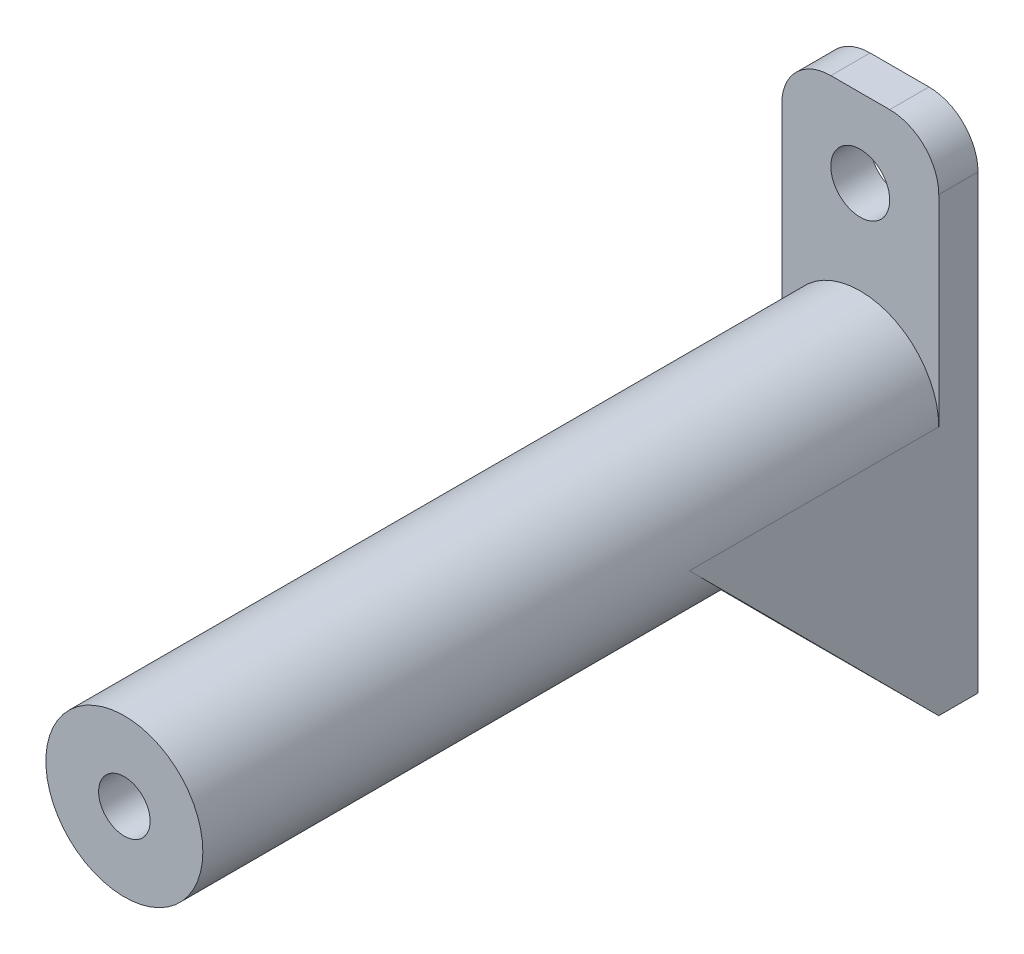
SolidWorks part; units mm, degrees
ref_plane "Front Plane" through (0, 0, 0) normal (0, 0, 1) x (1, 0, 0)
ref_plane "Top Plane" through (0, 0, 0) normal (0, 1, 0) x (1, 0, 0)
ref_plane "Right Plane" through (0, 0, 0) normal (1, 0, 0) x (0, 0, -1)
sketch "Sketch1" plane through (0, 0, 0) normal (0, 0, 1) x (1, 0, 0)
  line L0 (0, 17.5) -> (0, -17.5) construction
  line L1 (8, -25.5) -> (8, 25.5)
  line L2 (8, 25.5) -> (-8, 25.5)
  line L3 (-8, 25.5) -> (-8, -25.5)
  line L4 (-8, -25.5) -> (8, -25.5)
  line L5 (-8, 0) -> (8, 0) construction
  circle A0 centre (0, 17.5) radius 3
  circle A1 centre (0, -17.5) radius 3
  point P9 (8, 25.0328)
  dimension "D1" = 6
  dimension "D4" = 8
  dimension "D2" = 35
  dimension "D3" = 16
extrude "Boss-Extrude1" add sketch "Sketch1" along normal blind 4
sketch "Sketch2" plane through (0, 0, 4) normal (0, 0, 1) x (1, 0, 0)
  circle A0 centre (0, 0) radius 8
  dimension "D1" = 16
extrude "Boss-Extrude2" add sketch "Sketch2" along normal blind 75
sketch "Sketch4" plane through (8, 0, 0) normal (1, 0, 0) x (0, 0, -1)
  line L0 (-4, 0) -> (-29.4, 0)
  line L1 (-29.4, 0) -> (-4, -25.5)
  line L2 (-4, -25.5) -> (-4, 0)
  dimension "D1" = 25.4
extrude "Boss-Extrude3" add sketch "Sketch4" against normal blind 2
mirror "Mirror1" about plane through (0, 0, 0) normal (1, 0, 0) of "Boss-Extrude3"
sketch "Sketch5" plane through (0, 0, 79) normal (0, 0, 1) x (1, 0, 0)
  circle A0 centre (0, 0) radius 2.625
  dimension "D1" = 5.25
extrude "Cut-Extrude1" cut sketch "Sketch5" against normal blind 35
fillet "Fillet1" radius 5 2 edges at (8, 25.5, 2) (-8, 25.5, 2)
